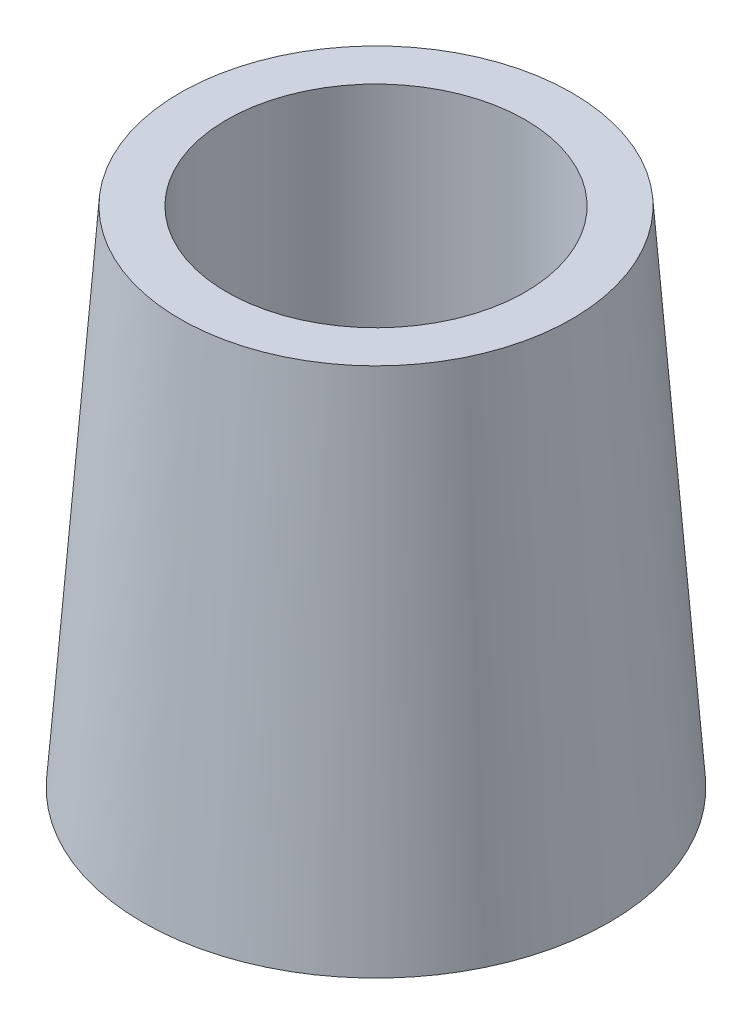
SolidWorks part; units mm, degrees
ref_plane "Front Plane" through (0, 0, 0) normal (0, 0, 1) x (1, 0, 0)
ref_plane "Top Plane" through (0, 0, 0) normal (0, 1, 0) x (1, 0, 0)
ref_plane "Right Plane" through (0, 0, 0) normal (1, 0, 0) x (0, 0, -1)
sketch "Sketch1" plane through (0, 0, 0) normal (0, 0, 1) x (1, 0, 0)
  line L0 (0, 0) -> (0, 27) construction
  line L1 (8, 27) -> (10.5, 27) construction
  line L2 (10.5, 27) -> (12.5, 0)
  line L3 (12.5, 0) -> (8, 0)
  line L4 (8, 0) -> (8, 27)
  line L5 (8, 27) -> (10.5, 27)
  point P5 (11.7726, 27)
  dimension "D1" = 27
  dimension "D2" = 25
  dimension "D3" = 16
  dimension "D4" = 21
revolve "Revolve1" add sketch "Sketch1" angle 360 about L0
